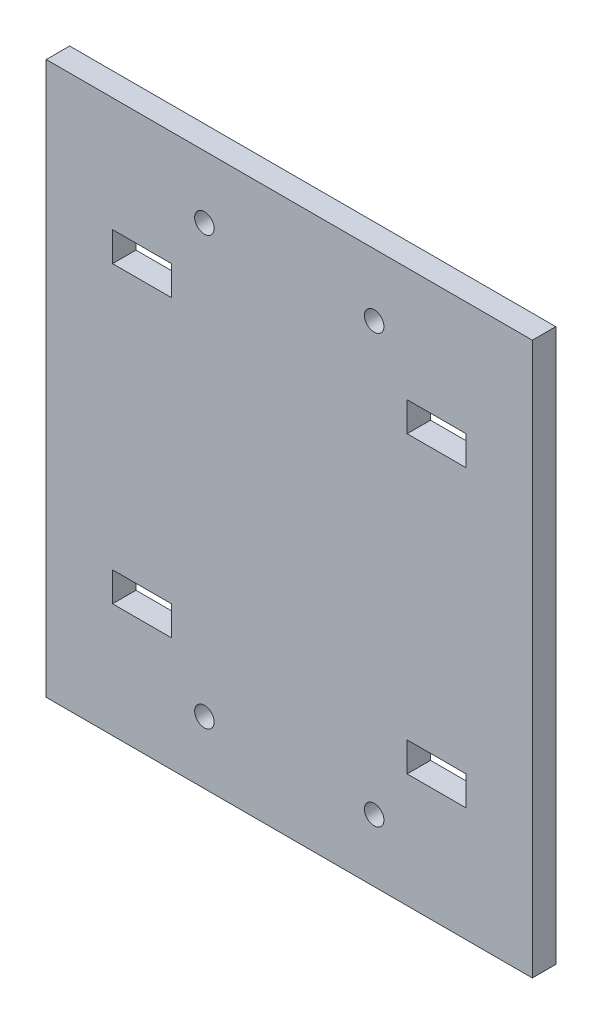
SolidWorks part; units mm, degrees
ref_plane "Front Plane" through (0, 0, 0) normal (0, 0, 1) x (1, 0, 0)
ref_plane "Top Plane" through (0, 0, 0) normal (0, 1, 0) x (1, 0, 0)
ref_plane "Right Plane" through (0, 0, 0) normal (1, 0, 0) x (0, 0, -1)
sketch "Sketch1" plane through (0, 0, 0) normal (0, 0, 1) x (1, 0, 0)
  line L0 (0, 33.4916) -> (0, -33.4916) construction
  line L1 (-43.0015, 0) -> (47.5957, 0) construction
  line L3 (-33, 37.5) -> (33, 37.5)
  line L4 (-33, 37.5) -> (-33, -37.5)
  line L5 (-33, -37.5) -> (33, -37.5)
  line L6 (33, 37.5) -> (33, -37.5)
  line L7 (-33, 37.5) -> (33, -37.5) construction
  line L8 (-33, -37.5) -> (33, 37.5) construction
  point P5 (0, 0)
  dimension "D1" = 75
  dimension "D2" = 66
extrude "Boss-Extrude1" add sketch "Sketch1" along normal blind 3.18
sketch "Sketch2" plane through (0, 0, 3.18) normal (0, 0, 1) x (1, 0, 0)
  line L0 (-11.525, 29.025) -> (11.525, 29.025) construction
  line L1 (11.525, 29.025) -> (11.525, -29.025) construction
  line L2 (11.525, -29.025) -> (-11.525, -29.025) construction
  line L3 (-11.525, -29.025) -> (-11.525, 29.025) construction
  line L7 (-11.525, 29.025) -> (11.525, -29.025) construction
  line L8 (11.525, 29.025) -> (-11.525, -29.025) construction
  line L9 (-20, 20) -> (-20, -20) construction
  line L10 (-24, 22) -> (-16, 22)
  line L11 (-24, 22) -> (-24, 18)
  line L12 (-24, 18) -> (-16, 18)
  line L13 (-16, 22) -> (-16, 18)
  line L14 (-24, 22) -> (-16, 18) construction
  line L15 (-24, 18) -> (-16, 22) construction
  line L16 (-24, -18) -> (-16, -18)
  line L17 (-24, -18) -> (-24, -22)
  line L18 (-24, -22) -> (-16, -22)
  line L19 (-16, -18) -> (-16, -22)
  line L20 (-24, -18) -> (-16, -22) construction
  line L21 (-24, -22) -> (-16, -18) construction
  line L22 (16, -18) -> (24, -18)
  line L23 (16, -18) -> (16, -22)
  line L24 (16, -22) -> (24, -22)
  line L25 (24, -18) -> (24, -22)
  line L26 (16, -18) -> (24, -22) construction
  line L27 (16, -22) -> (24, -18) construction
  line L28 (16, 22) -> (24, 22)
  line L29 (16, 22) -> (16, 18)
  line L30 (16, 18) -> (24, 18)
  line L31 (24, 22) -> (24, 18)
  line L32 (16, 22) -> (24, 18) construction
  line L33 (16, 18) -> (24, 22) construction
  line L34 (-20, -20) -> (20, -20) construction
  line L35 (20, -20) -> (20, 20) construction
  line L36 (20, 20) -> (-20, 20) construction
  line L37 (-20, -20) -> (20, 20) construction
  line L38 (-20, 20) -> (20, -20) construction
  circle A0 centre (-11.525, 29.025) radius 1.325
  circle A1 centre (-11.525, -29.025) radius 1.325
  circle A2 centre (11.525, -29.025) radius 1.325
  circle A3 centre (11.525, 29.025) radius 1.325
  point P8 (0, 0)
  point P9 (-20, 20)
  point P17 (-20, -20)
  point P22 (20, -20)
  point P27 (20, 20)
  point P36 (0, 0)
  dimension "D3" = 2.65
  dimension "D1" = 23.05
  dimension "D2" = 58.05
  dimension "D4" = 40
  dimension "D5" = 40
  dimension "D6" = 4
  dimension "D7" = 8
extrude "Cut-Extrude1" cut sketch "Sketch2" against normal through all
